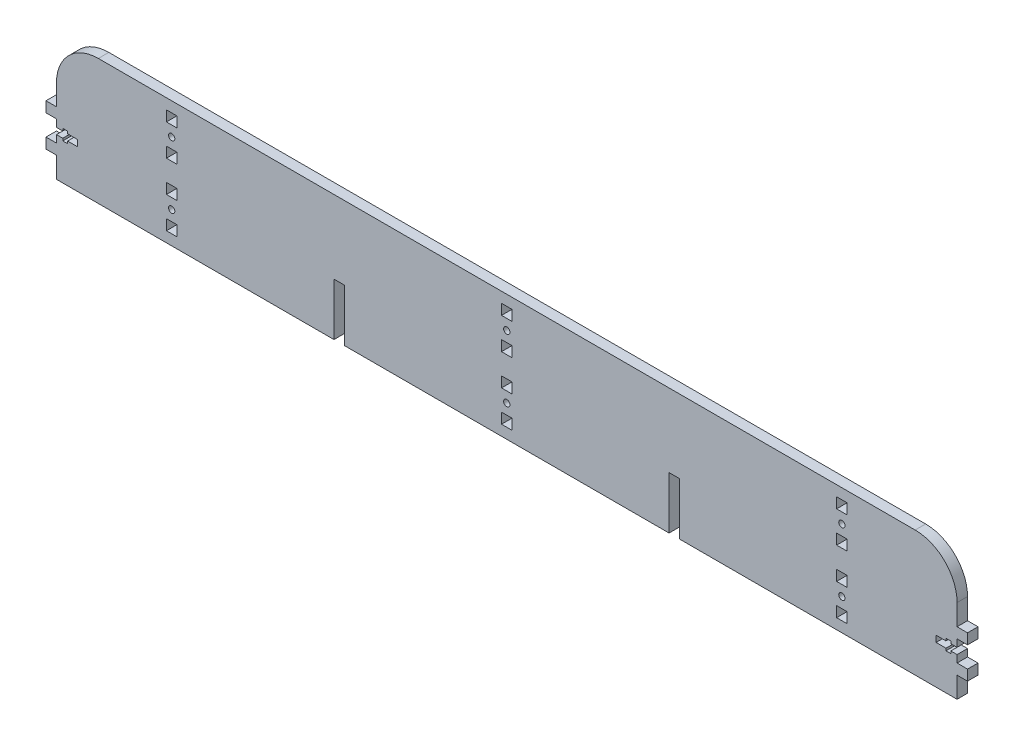
SolidWorks part; units mm, degrees
ref_plane "Plan de face" through (0, 0, 0) normal (0, 0, 1) x (1, 0, 0)
ref_plane "Plan de dessus" through (0, 0, 0) normal (0, 1, 0) x (1, 0, 0)
ref_plane "Plan de droite" through (0, 0, 0) normal (1, 0, 0) x (0, 0, -1)
sketch "Esquisse1" plane through (0, 0, 0) normal (0, 0, 1) x (1, 0, 0)
  line L0 (0, 0) -> (0, 60) construction
  line L1 (0, 60) -> (430, 60) construction
  line L2 (430, 60) -> (430, 0) construction
  line L3 (430, 0) -> (0, 0) construction
  line L4 (135, 0) -> (135, 60) construction
  line L5 (295, 60) -> (295, 0) construction
  line L6 (215, 0) -> (215, 60) construction
  line L7 (0, 20) -> (11.2208, 20) construction
  line L8 (0, 21.5) -> (0, 25)
  line L9 (-5, 25) -> (-5, 30)
  line L10 (-5, 30) -> (0, 30)
  line L11 (-5, 25) -> (0, 25)
  line L12 (0, 18.5) -> (0, 15)
  line L13 (0, 15) -> (-5, 15)
  line L14 (-5, 15) -> (-5, 10)
  line L15 (-5, 10) -> (0, 10)
  line L16 (0, 21.5) -> (0, 18.5) construction
  line L17 (0, 18.5) -> (3, 18.5)
  line L18 (5.3, 18.5) -> (5.3, 17.4)
  line L19 (3, 22.6) -> (5.3, 22.6)
  line L20 (3, 17.4) -> (3, 18.5)
  line L21 (5.3, 18.5) -> (10, 18.5)
  line L22 (10, 18.5) -> (10, 21.5)
  line L23 (10, 21.5) -> (5.3, 21.5)
  line L24 (3, 21.5) -> (3, 22.6)
  line L25 (5.3, 17.4) -> (3, 17.4)
  line L26 (5.3, 22.6) -> (5.3, 21.5)
  line L27 (3, 21.5) -> (0, 21.5)
  line L28 (10, 20) -> (0, 20) construction
  line L29 (435, 30) -> (430, 30)
  line L30 (435, 25) -> (435, 30)
  line L31 (435, 25) -> (430, 25)
  line L32 (430, 21.5) -> (430, 25)
  line L33 (427, 21.5) -> (430, 21.5)
  line L34 (427, 21.5) -> (427, 22.6)
  line L35 (427, 22.6) -> (424.7, 22.6)
  line L36 (424.7, 22.6) -> (424.7, 21.5)
  line L37 (420, 21.5) -> (424.7, 21.5)
  line L38 (420, 18.5) -> (420, 21.5)
  line L39 (424.7, 18.5) -> (420, 18.5)
  line L40 (424.7, 18.5) -> (424.7, 17.4)
  line L41 (424.7, 17.4) -> (427, 17.4)
  line L42 (427, 17.4) -> (427, 18.5)
  line L43 (430, 18.5) -> (427, 18.5)
  line L44 (430, 18.5) -> (430, 15)
  line L45 (430, 15) -> (435, 15)
  line L46 (435, 15) -> (435, 10)
  line L47 (435, 10) -> (430, 10)
  line L48 (0, 0) -> (0, 10)
  line L49 (0, 30) -> (0, 60)
  line L50 (430, 0) -> (430, 10)
  line L51 (430, 30) -> (430, 60)
  line L55 (297.5, 25) -> (292.5, 25)
  line L59 (132.5, 25) -> (137.5, 25)
  line L62 (430, 0) -> (297.5, 0)
  line L63 (297.5, 0) -> (297.5, 25)
  line L64 (292.5, 25) -> (292.5, 0)
  line L65 (292.5, 0) -> (137.5, 0)
  line L66 (137.5, 0) -> (137.5, 25)
  line L67 (132.5, 25) -> (132.5, 0)
  line L68 (132.5, 0) -> (0, 0)
  line L69 (0, 60) -> (430, 60)
  line L70 (55, 60) -> (55, 0) construction
  line L71 (375, 0) -> (375, 60) construction
  point P67 (0, 0)
  point P68 (0, 0)
  point P69 (0, 0)
  point P70 (0, 0)
  line B0 (375, 10) -> (375, 20) construction
  line B1 (372.5, 10) -> (372.5, 5)
  line B2 (372.5, 10) -> (377.5, 10)
  line B3 (377.5, 10) -> (377.5, 5)
  line B4 (372.5, 5) -> (377.5, 5)
  line B5 (372.5, 20) -> (372.5, 25)
  line B6 (372.5, 20) -> (377.5, 20)
  line B7 (377.5, 20) -> (377.5, 25)
  line B8 (372.5, 25) -> (377.5, 25)
  line B9 (375, 15) -> (368.0276, 15) construction
  circle B10 centre (375, 15) radius 1.5
  line B11 (375, 40) -> (375, 50) construction
  line B12 (372.5, 40) -> (372.5, 35)
  line B13 (372.5, 40) -> (377.5, 40)
  line B14 (377.5, 40) -> (377.5, 35)
  line B15 (372.5, 35) -> (377.5, 35)
  line B16 (372.5, 50) -> (372.5, 55)
  line B17 (372.5, 50) -> (377.5, 50)
  line B18 (377.5, 50) -> (377.5, 55)
  line B19 (372.5, 55) -> (377.5, 55)
  line B20 (375, 45) -> (368.0276, 45) construction
  circle B21 centre (375, 45) radius 1.5
  line B22 (215, 10) -> (215, 20) construction
  line B23 (212.5, 10) -> (212.5, 5)
  line B24 (212.5, 10) -> (217.5, 10)
  line B25 (217.5, 10) -> (217.5, 5)
  line B26 (212.5, 5) -> (217.5, 5)
  line B27 (212.5, 20) -> (212.5, 25)
  line B28 (212.5, 20) -> (217.5, 20)
  line B29 (217.5, 20) -> (217.5, 25)
  line B30 (212.5, 25) -> (217.5, 25)
  line B31 (215, 15) -> (208.0276, 15) construction
  circle B32 centre (215, 15) radius 1.5
  line B33 (215, 40) -> (215, 50) construction
  line B34 (212.5, 40) -> (212.5, 35)
  line B35 (212.5, 40) -> (217.5, 40)
  line B36 (217.5, 40) -> (217.5, 35)
  line B37 (212.5, 35) -> (217.5, 35)
  line B38 (212.5, 50) -> (212.5, 55)
  line B39 (212.5, 50) -> (217.5, 50)
  line B40 (217.5, 50) -> (217.5, 55)
  line B41 (212.5, 55) -> (217.5, 55)
  line B42 (215, 45) -> (208.0276, 45) construction
  circle B43 centre (215, 45) radius 1.5
  line B44 (55, 10) -> (55, 20) construction
  line B45 (52.5, 10) -> (52.5, 5)
  line B46 (52.5, 10) -> (57.5, 10)
  line B47 (57.5, 10) -> (57.5, 5)
  line B48 (52.5, 5) -> (57.5, 5)
  line B49 (52.5, 20) -> (52.5, 25)
  line B50 (52.5, 20) -> (57.5, 20)
  line B51 (57.5, 20) -> (57.5, 25)
  line B52 (52.5, 25) -> (57.5, 25)
  line B53 (55, 15) -> (48.0276, 15) construction
  circle B54 centre (55, 15) radius 1.5
  line B55 (55, 40) -> (55, 50) construction
  line B56 (52.5, 40) -> (52.5, 35)
  line B57 (52.5, 40) -> (57.5, 40)
  line B58 (57.5, 40) -> (57.5, 35)
  line B59 (52.5, 35) -> (57.5, 35)
  line B60 (52.5, 50) -> (52.5, 55)
  line B61 (52.5, 50) -> (57.5, 50)
  line B62 (57.5, 50) -> (57.5, 55)
  line B63 (52.5, 55) -> (57.5, 55)
  line B64 (55, 45) -> (48.0276, 45) construction
  circle B65 centre (55, 45) radius 1.5
  dimension "D1" = 135
  dimension "D2" = 5
  dimension "D3" = 20
  dimension "D4" = 10
  dimension "D5" = 5
  dimension "D6" = 5
  dimension "D7" = 5.2
  dimension "D8" = 3
  dimension "D9" = 2.3
  dimension "D10" = 3
  dimension "D11" = 10
  dimension "D12" = 430
  dimension "D13" = 160
  dimension "D14" = 30
  dimension "D15" = 60
  dimension "D16" = 5
sketch_block_instance "Trou M3 plots 5mm-1"
sketch_block "Trou M3 plots 5mm" parameters "D2"=3, "D1"=5, "D3"=5, "D4"=10
sketch_block_instance "Trou M3 plots 5mm-3"
sketch_block_instance "Trou M3 plots 5mm-4"
sketch_block_instance "Trou M3 plots 5mm-5"
sketch_block_instance "Trou M3 plots 5mm-6"
sketch_block_instance "Trou M3 plots 5mm-7"
extrude "Boss.-Extru.1" add sketch "Esquisse1" along normal blind 5
fillet "Congé1" radius 20 2 edges at (430, 60, 2.5) (0, 60, 2.5)
